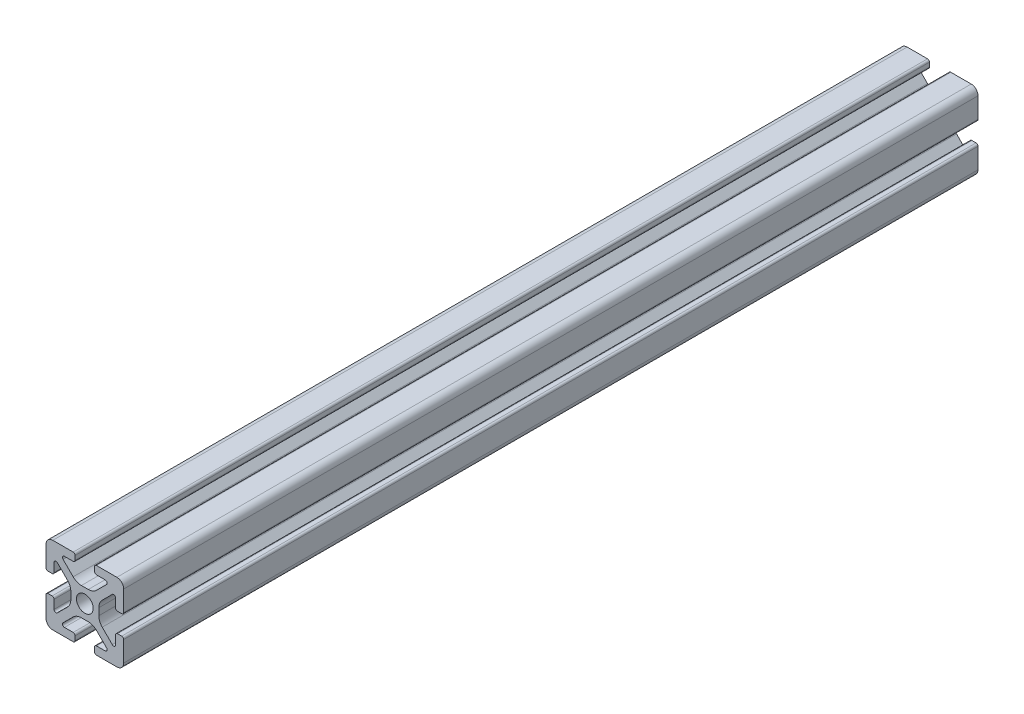
SolidWorks part; units mm, degrees
ref_plane "Front Plane" through (0, 0, 0) normal (0, 0, 1) x (1, 0, 0)
ref_plane "Top Plane" through (0, 0, 0) normal (0, 1, 0) x (1, 0, 0)
ref_plane "Right Plane" through (0, 0, 0) normal (1, 0, 0) x (0, 0, -1)
sketch "Sketch2" plane through (0, 0, 0) normal (0, 0, 1) x (1, 0, 0)
  line L0 (0, 10) -> (0, -10) construction
  line L1 (-10, 0) -> (10, 0) construction
  line L2 (2.5, -10) -> (10, -10)
  line L3 (10, -10) -> (10, -2.5)
  line L4 (2.5, -10) -> (2.5, -7.9246)
  line L5 (2.5, -7.9246) -> (6.4571, -7.9246)
  line L6 (6.4571, -7.9246) -> (2.1325, -3.6)
  line L7 (0, 0) -> (10, -10) construction
  line L8 (10, -2.5) -> (7.9246, -2.5)
  line L9 (7.9246, -2.5) -> (7.9246, -6.4571)
  line L10 (7.9246, -6.4571) -> (3.6, -2.1325)
  line L11 (5.7623, -4.2948) -> (4.2948, -5.7623) construction
  circle A0 centre (0, 0) radius 2.15
  arc A1 (5.25, -7.9246) -> (5.6036, -7.0711) centre (5.25, -7.4246) ccw construction
  point P8 (0, -3.6)
  point P16 (5.0286, -5.0286)
  dimension "Center Hole Diameter" = 4.3
  dimension "D3" = 0.5
  dimension "Rail Height" = 20
  dimension "Rail Width" = 20
  dimension "T-Slot Width" = 5
  dimension "Slot Depth" = 6.4
  dimension "Slot Inner Width" = 11.5
sketch "Sketch3" plane through (0, 0, 0) normal (1, 0, 0) x (0, 0, -1)
  line L0 (-76.2, -10) -> (76.2, -10) construction
  line L1 (-50.8, 0) -> (50.8, 0) construction
  line L2 (0, 10) -> (0, -10) construction
  line L3 (0, 10) -> (0, -10) construction
  point P6 (-50.8, 0)
  point P8 (50.8, 0)
  dimension "D1" = 25.4
  dimension "Length" = 152.4
sketch "Sketch4" plane through (0, 0, 0) normal (0, 0, 1) x (1, 0, 0)
  line L0 (3, -10) -> (8.25, -10)
  line L1 (2.5, -10) -> (10, -10) construction
  line L2 (2.5, -10) -> (2.5, -7.9246) construction
  line L3 (2.5, -7.9246) -> (6.4571, -7.9246) construction
  line L4 (2.5, -8.4246) -> (2.5, -9.5)
  line L5 (3, -7.9246) -> (5.25, -7.9246)
  line L6 (0, -3.6) -> (0.8898, -3.6)
  line L7 (6.4571, -7.9246) -> (2.1325, -3.6) construction
  line L8 (3.0112, -4.4787) -> (5.6036, -7.0711)
  line L9 (10, -10) -> (10, -2.5) construction
  line L10 (7.9246, -6.4571) -> (3.6, -2.1325) construction
  line L11 (7.9246, -2.5) -> (7.9246, -6.4571) construction
  line L12 (7.9246, -5.25) -> (7.9246, -3)
  line L13 (10, -2.5) -> (7.9246, -2.5) construction
  line L14 (8.4246, -2.5) -> (9.5, -2.5)
  line L15 (10, -3) -> (10, -8.25)
  line L16 (7.0711, -5.6036) -> (4.4787, -3.0112)
  line L17 (3.6, 0) -> (3.6, -0.8898)
  line L18 (-10, 0) -> (10, 0) construction
  line L19 (0, -3.6) -> (0, -2.15)
  line L20 (0, 10) -> (0, -10) construction
  line L21 (3.6, 0) -> (2.15, 0)
  arc A0 (2.5, -9.5) -> (3, -10) centre (3, -9.5) ccw
  arc A1 (5.25, -7.9246) -> (5.6036, -7.0711) centre (5.25, -7.4246) ccw construction
  arc A2 (2.5, -8.4246) -> (3, -7.9246) centre (3, -8.4246) cw
  arc A3 (5.25, -7.9246) -> (5.6036, -7.0711) centre (5.25, -7.4246) ccw
  arc A4 (0.8898, -3.6) -> (3.0112, -4.4787) centre (0.8898, -6.6) cw
  arc A5 (8.25, -10) -> (10, -8.25) centre (8.25, -8.25) ccw
  arc A6 (7.0711, -5.6036) -> (7.9246, -5.25) centre (7.4246, -5.25) ccw
  arc A7 (7.9246, -3) -> (8.4246, -2.5) centre (8.4246, -3) cw
  arc A8 (9.5, -2.5) -> (10, -3) centre (9.5, -3) cw
  arc A9 (4.4787, -3.0112) -> (3.6, -0.8898) centre (6.6, -0.8898) cw
  circle A10 centre (0, 0) radius 2.15 construction
  arc A11 (0, -2.15) -> (2.15, 0) centre (0, 0) ccw
  dimension "D1" = 1.75
  dimension "D2" = 3
extrude "Boss-Extrude1" add sketch "Sketch4" along normal mid plane 220
mirror "Mirror1" about plane through (0, 0, 0) normal (1, 0, 0) of bodies 134
mirror "Mirror2" about plane through (0, 0, 0) normal (0, 1, 0) of bodies 135
equation "\"D3@Sketch2\"=\"T-Slot Width@Sketch2\"*0.1"
equation "\"D1@Sketch4\"=\"D3@Sketch2\"*3.5"
equation "\"D2@Sketch4\"=\"D3@Sketch2\"*6"
equation "\"D1@Boss-Extrude1\"=110"
